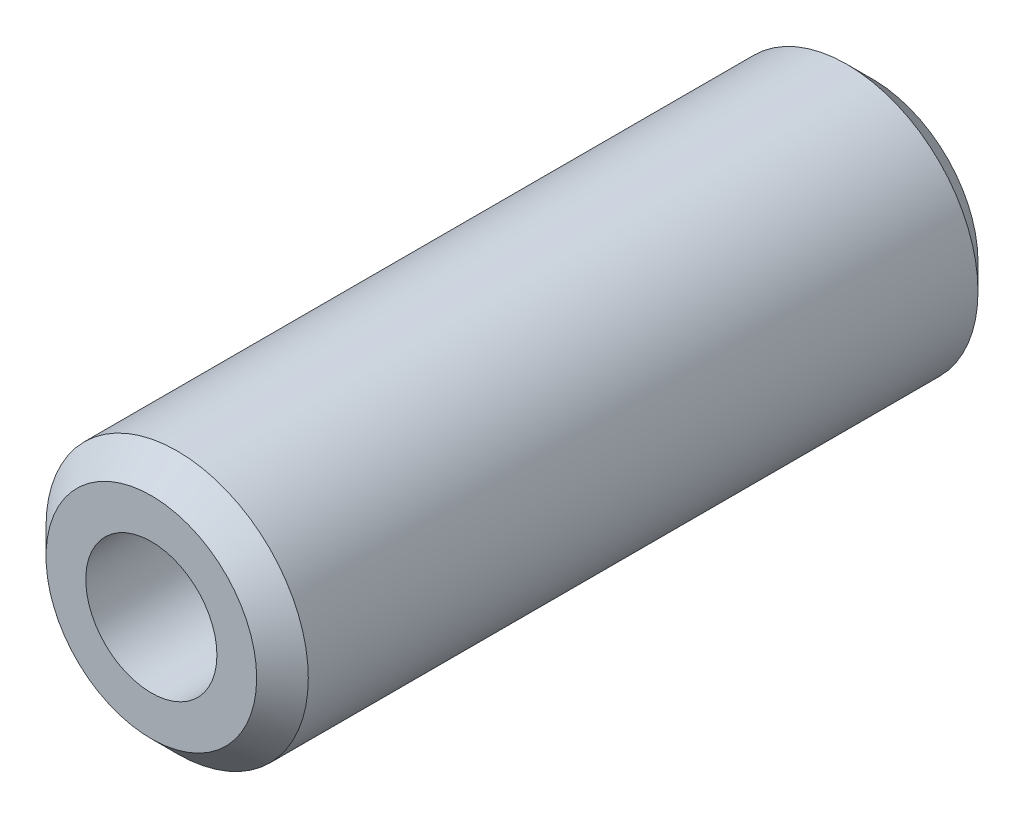
SolidWorks part; units mm, degrees
material "AISI 1035 Steel (SS)"
ref_plane "Front Plane" through (0, 0, 0) normal (0, 0, 1) x (1, 0, 0)
ref_plane "Top Plane" through (0, 0, 0) normal (0, 1, 0) x (1, 0, 0)
ref_plane "Right Plane" through (0, 0, 0) normal (1, 0, 0) x (0, 0, -1)
sketch "Sketch2" plane through (0, 0, 0) normal (0, 0, 1) x (1, 0, 0)
  circle A0 centre (0, 0) radius 6.35
  circle A1 centre (0, 0) radius 12.7
  dimension "D1" = 12.7
  dimension "D2" = 25.4
extrude "Boss-Extrude1" add sketch "Sketch2" along normal mid plane 69.85
chamfer "Chamfer1" distance 2.5 angle 45 2 edges at (12.7, 0, -34.925) (12.7, 0, 34.925)
